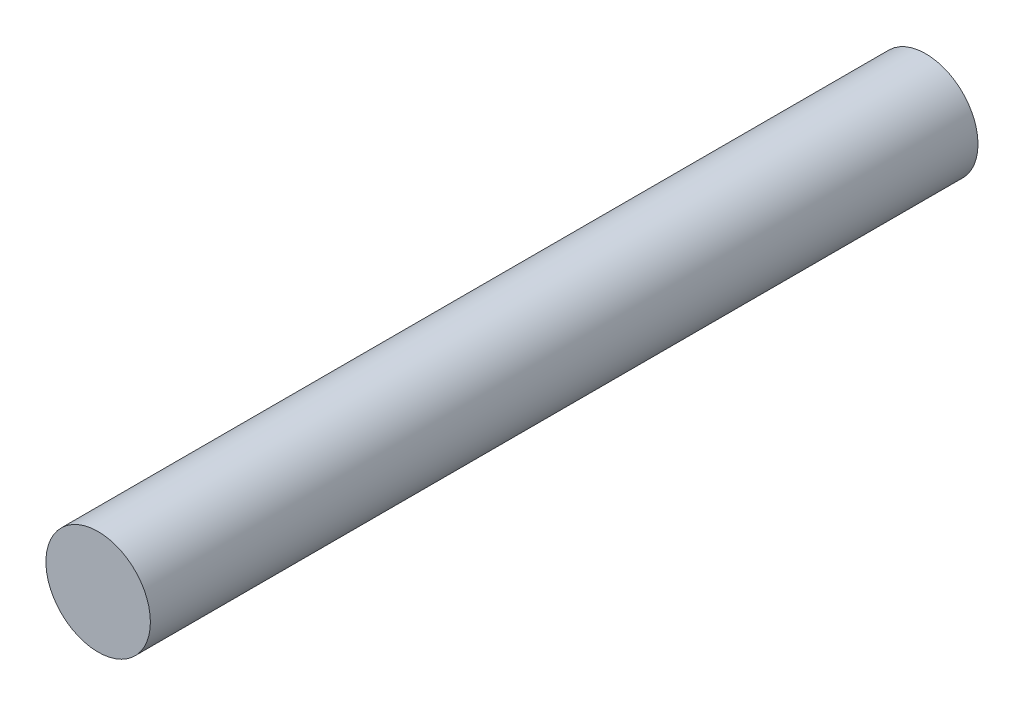
SolidWorks part; units mm, degrees
material "Pure Gold"
ref_plane "Front Plane" through (0, 0, 0) normal (0, 0, 1) x (1, 0, 0)
ref_plane "Top Plane" through (0, 0, 0) normal (0, 1, 0) x (1, 0, 0)
ref_plane "Right Plane" through (0, 0, 0) normal (1, 0, 0) x (0, 0, -1)
sketch "Sketch1" plane through (0, 0, 0) normal (0, 0, 1) x (1, 0, 0)
  circle A0 centre (0, 0) radius 0.6477
  dimension "D1" = 1.2954
extrude "Boss-Extrude1" add sketch "Sketch1" along normal blind 10.2616
